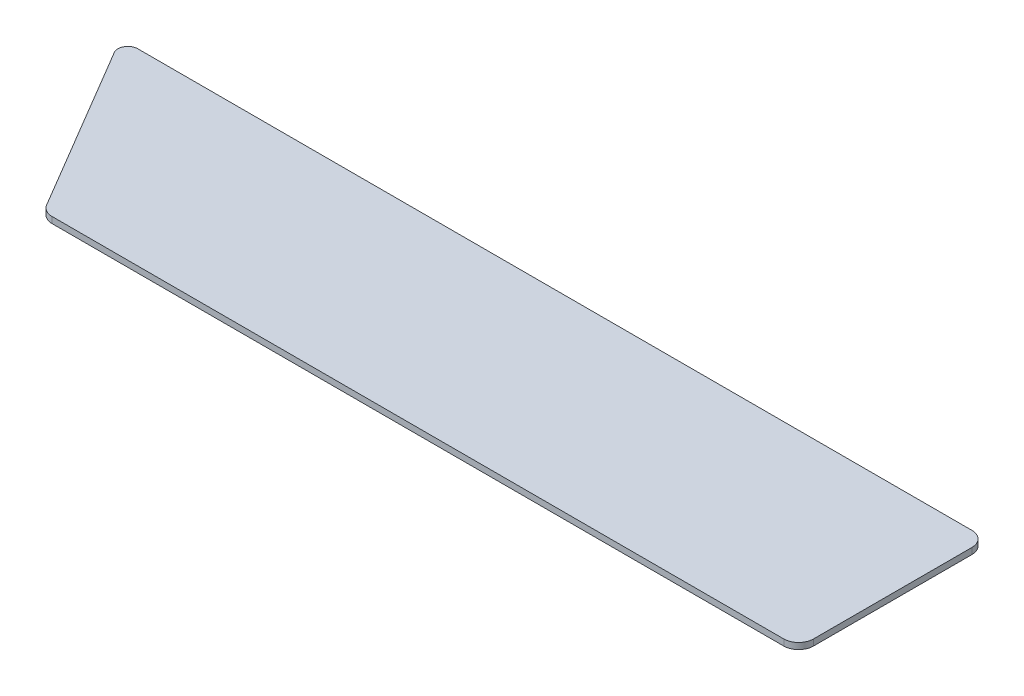
SolidWorks part; units mm, degrees
ref_plane "Front" through (0, 0, 0) normal (0, 0, 1) x (1, 0, 0)
ref_plane "Top" through (0, 0, 0) normal (0, 1, 0) x (1, 0, 0)
ref_plane "Right" through (0, 0, 0) normal (1, 0, 0) x (0, 0, -1)
sketch "Sketch2" plane through (0, 0, 0) normal (0, 1, 0) x (1, 0, 0)
  line L0 (0, 96.52) -> (57.15, 0)
  line L1 (0, 0) -> (444.5, 0)
  line L2 (0, 0) -> (0, 96.52)
  line L3 (0, 96.52) -> (444.5, 96.52)
  line L4 (444.5, 0) -> (444.5, 96.52)
  point P5 (0, 0)
  point P7 (0, 0)
  dimension "D1" = 444.5
  dimension "D2" = 96.52
extrude "Boss-Extrude2" add sketch "Sketch2" along normal blind 3.175 contours L1 L4 L3 L0
fillet "Fillet3" radius 7.62 3 edges at (444.5, 1.5875, -96.52) (444.5, 1.5875, 0) (57.15, 1.5875, 0)
fillet "Fillet4" radius 5.08 1 edges at (0, 1.5875, -96.52)
